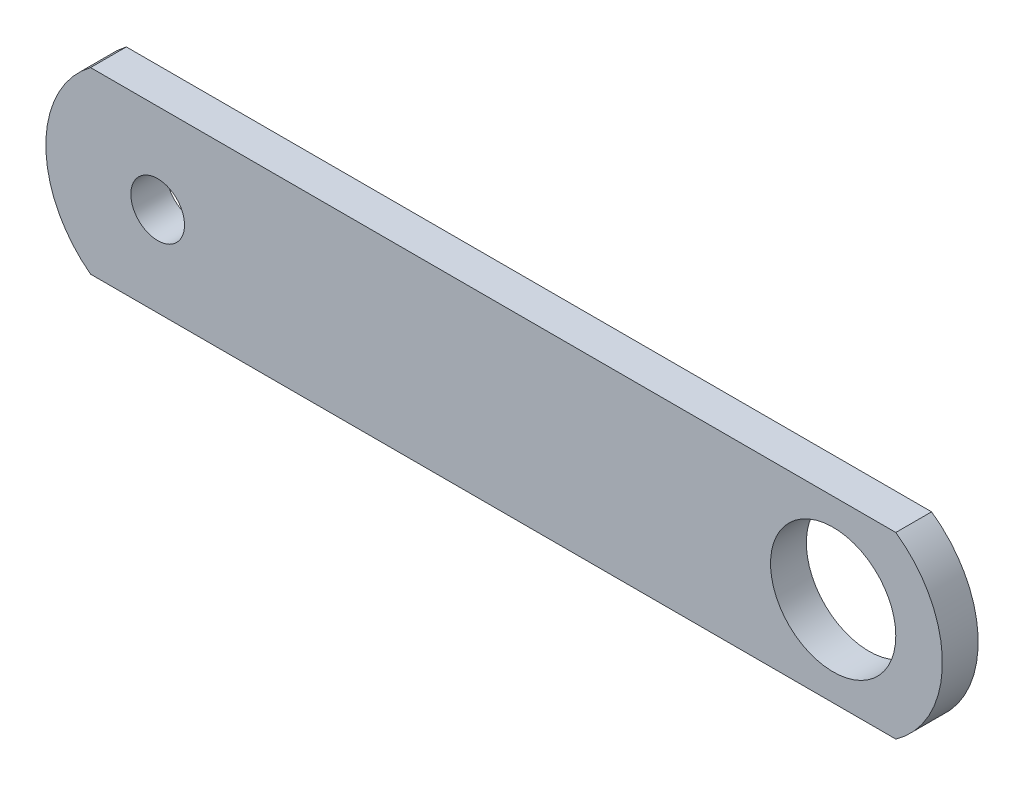
SolidWorks part; units mm, degrees
ref_plane "Front Plane" through (0, 0, 0) normal (0, 0, 1) x (1, 0, 0)
ref_plane "Top Plane" through (0, 0, 0) normal (0, 1, 0) x (1, 0, 0)
ref_plane "Right Plane" through (0, 0, 0) normal (1, 0, 0) x (0, 0, -1)
sketch "Sketch2" plane through (0, 0, 0) normal (0, 0, 1) x (1, 0, 0)
  line L1 (-45, -10) -> (45, -10)
  line L3 (-45, 10) -> (45, 10)
  line L5 (-45, -10) -> (45, 10) construction
  line L6 (-45, 10) -> (45, -10) construction
  circle A0 centre (-37.5, 0) radius 3
  circle A1 centre (38, 0) radius 7
  arc A2 (-45, -10) -> (-45, 10) centre (-37.5, 0) cw
  arc A3 (45, 10) -> (45, -10) centre (38, 0) cw
  point P0 (0, 0)
  dimension "D3" = 6
  dimension "D4" = 14
  dimension "D1" = 90
  dimension "D2" = 20
extrude "Boss-Extrude1" add sketch "Sketch2" along normal blind 4
